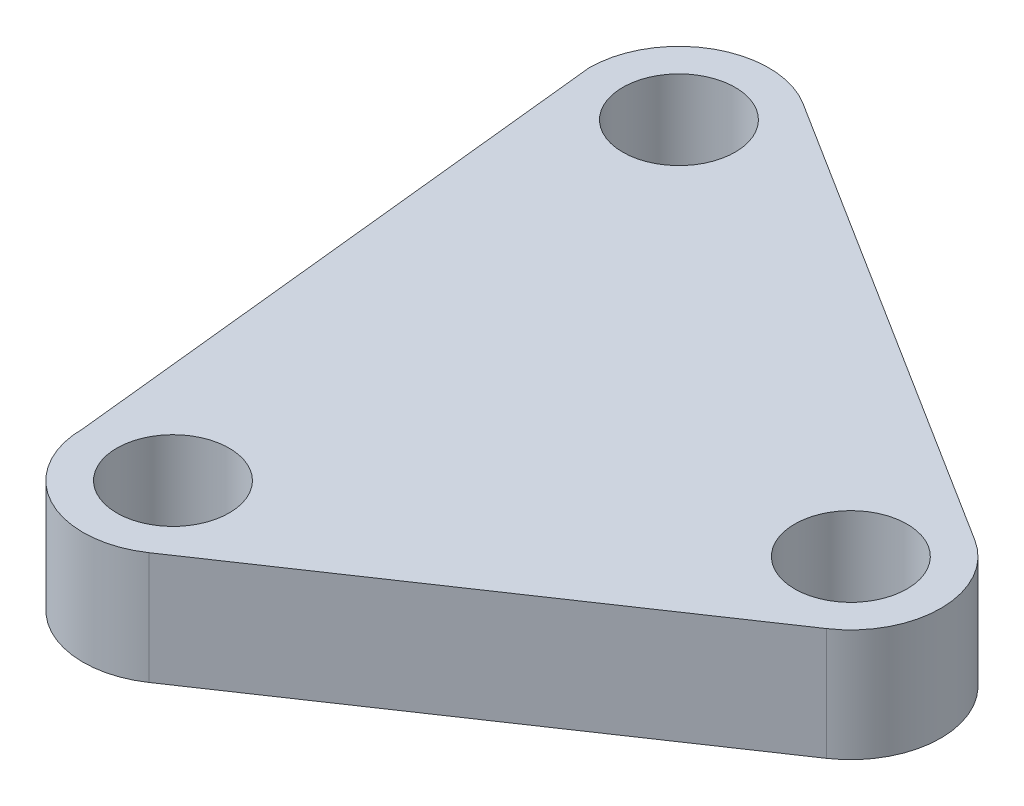
SolidWorks part; units mm, degrees
ref_plane "Front Plane" through (0, 0, 0) normal (0, 0, 1) x (1, 0, 0)
ref_plane "Top Plane" through (0, 0, 0) normal (0, 1, 0) x (1, 0, 0)
ref_plane "Right Plane" through (0, 0, 0) normal (1, 0, 0) x (0, 0, -1)
sketch "Sketch1" plane through (0, 0, 0) normal (0, 1, 0) x (1, 0, 0)
  line L0 (20.6457, -13) -> (0, 0)
  line L1 (0, 0) -> (2.6457, -25.15)
  line L2 (2.6457, -25.15) -> (20.6457, -13)
  line L3 (-4, 0) -> (-1.3543, -25.15)
  line L4 (22.8836, -16.3154) -> (4.8836, -28.4654)
  line L5 (2.1314, 3.3849) -> (22.777, -9.6151)
  circle A0 centre (0, 0) radius 2.5
  circle A1 centre (20.6457, -13) radius 2.5
  circle A2 centre (2.6457, -25.15) radius 2.5
  circle A3 centre (0, 0) radius 4
  circle A4 centre (20.6457, -13) radius 4
  circle A5 centre (2.6457, -25.15) radius 4
  point P16 (2.1314, 3.3849)
  dimension "D9" = 5
  dimension "D10" = 8
  dimension "D1" = 24.3976
  dimension "D2" = 25.2888
  dimension "D3" = 21.7169
  dimension "D4" = 61.986
  dimension "D5" = 51.797
  dimension "D6" = 66.217
  dimension "D7" = 0
  dimension "D8" = 13
extrude "Boss-Extrude1" add sketch "Sketch1" along normal blind 5 contours A5 L1 A3 L3 | A4 L5 A3 L0 | L0 A3 L3 L1 A0 | L1 A3 L0 A0 | A5 L2 A4 L0 A3 L1 | A5 L4 A4 L2 | A5 L2 A2 L1 | L2 A5 L1 A2 | A4 L0 A1 L2 | L0 A4 L2 A1
